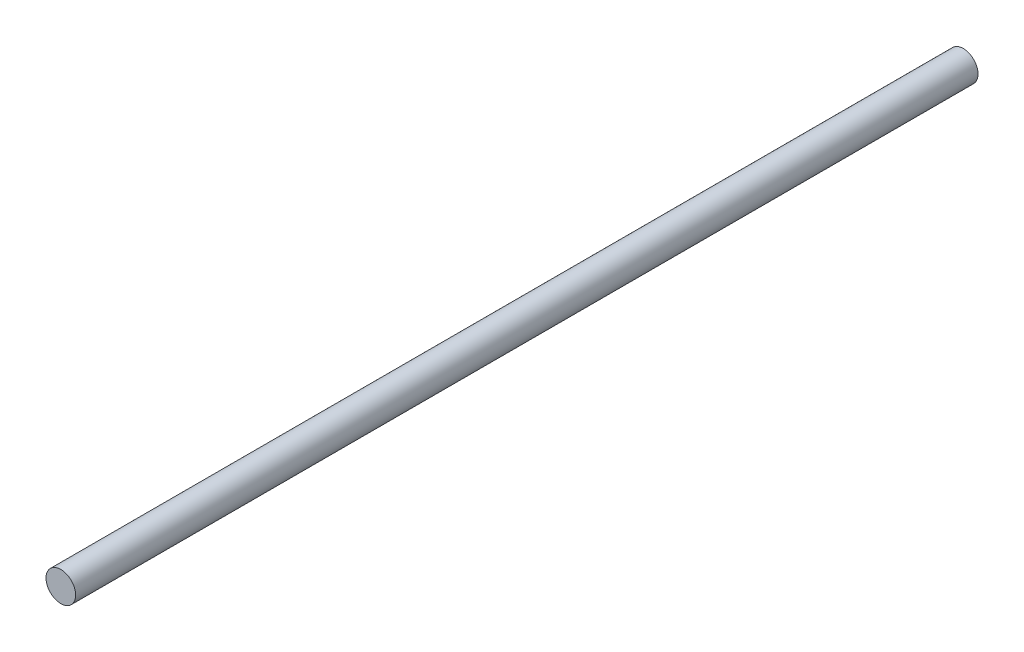
SolidWorks part; units mm, degrees
ref_plane "Front Plane" through (0, 0, 0) normal (0, 0, 1) x (1, 0, 0)
ref_plane "Top Plane" through (0, 0, 0) normal (0, 1, 0) x (1, 0, 0)
ref_plane "Right Plane" through (0, 0, 0) normal (1, 0, 0) x (0, 0, -1)
sketch "Sketch1" plane through (0, 0, 0) normal (0, 0, 1) x (1, 0, 0)
  circle A0 centre (0, 0) radius 1.5
  dimension "D1" = 3
extrude "Boss-Extrude1" add sketch "Sketch1" along normal blind 91.4
